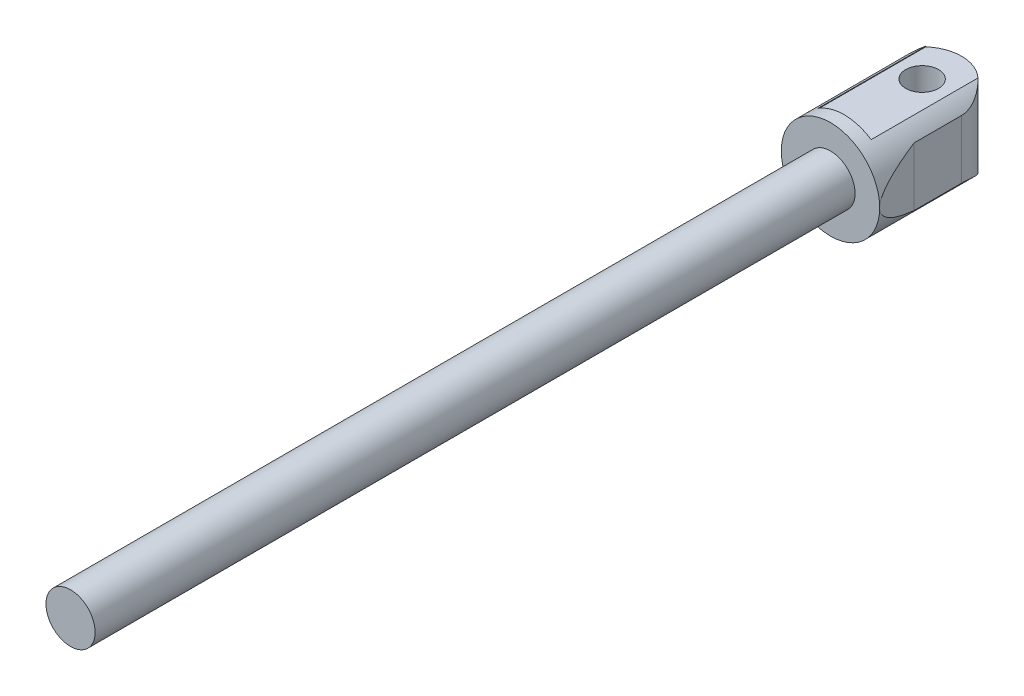
SolidWorks part; units mm, degrees
ref_plane "Front Plane" through (0, 0, 0) normal (0, 0, 1) x (1, 0, 0)
ref_plane "Top Plane" through (0, 0, 0) normal (0, 1, 0) x (1, 0, 0)
ref_plane "Right Plane" through (0, 0, 0) normal (1, 0, 0) x (0, 0, -1)
sketch "Sketch1" plane through (0, 0, 0) normal (0, 0, 1) x (1, 0, 0)
  circle A0 centre (0, 0) radius 37.5
  dimension "D1" = 75
extrude "Boss-Extrude1" add sketch "Sketch1" along normal mid plane 1159
sketch "Sketch2" plane through (0, 0, -579.5) normal (0, 0, -1) x (-1, 0, 0)
  circle A0 centre (0, 0) radius 75
  dimension "D1" = 150
extrude "Boss-Extrude2" add sketch "Sketch2" along normal blind 200
sketch "Sketch3" plane through (0, 0, 0) normal (0, 1, 0) x (1, 0, 0)
  line L0 (75, 779.5) -> (-75, 779.5) construction
  line L1 (60.24, 719.26) -> (60.24, 646.55)
  line L2 (60.24, 646.55) -> (75, 579.5)
  line L3 (75, 579.5) -> (75, 779.5) construction
  line L4 (0, 779.5) -> (0, 579.5) construction
  line L5 (-37.5, 579.5) -> (37.5, 579.5) construction
  line L6 (-60.24, 646.55) -> (-75, 579.5)
  line L7 (-60.24, 719.26) -> (-60.24, 646.55)
  line L8 (75, 579.5) -> (150.1252, 579.5)
  line L9 (150.1252, 579.5) -> (155.1056, 831.5442)
  line L10 (155.1056, 831.5442) -> (-155.8015, 837.6877)
  line L11 (-155.8015, 837.6877) -> (-75, 579.5)
  arc A0 (60.24, 719.26) -> (-60.24, 719.26) centre (0, 719.26) ccw
  circle A1 centre (0, 719.26) radius 25
  dimension "D1" = 120.48
  dimension "D2" = 50
  dimension "D3" = 72.71
extrude "Cut-Extrude1" cut sketch "Sketch3" against normal mid plane 200
sketch "Sketch4" plane through (60.24, 0, 0) normal (1, 0, 0) x (0, 0, -1)
  line L0 (579.5, 75) -> (579.5, 0) construction
  line L1 (600.36, 62.67) -> (861.3059, 62.67)
  line L2 (600.36, 62.67) -> (600.36, 138.4165)
  line L3 (600.36, 138.4165) -> (861.3059, 138.4165)
  line L4 (861.3059, 62.67) -> (861.3059, 138.4165)
  line L5 (694.26, 75) -> (579.5, 75) construction
  line L6 (779.5, 0) -> (529.4907, 0) construction
  line L7 (779.5, -75) -> (779.5, 75) construction
  line L8 (600.36, -138.4165) -> (861.3059, -138.4165)
  line L9 (861.3059, -62.67) -> (861.3059, -138.4165)
  line L10 (600.36, -62.67) -> (861.3059, -62.67)
  line L11 (600.36, -62.67) -> (600.36, -138.4165)
  dimension "D1" = 20.86
  dimension "D2" = 12.33
extrude "Cut-Extrude2" cut sketch "Sketch4" against normal mid plane 200
